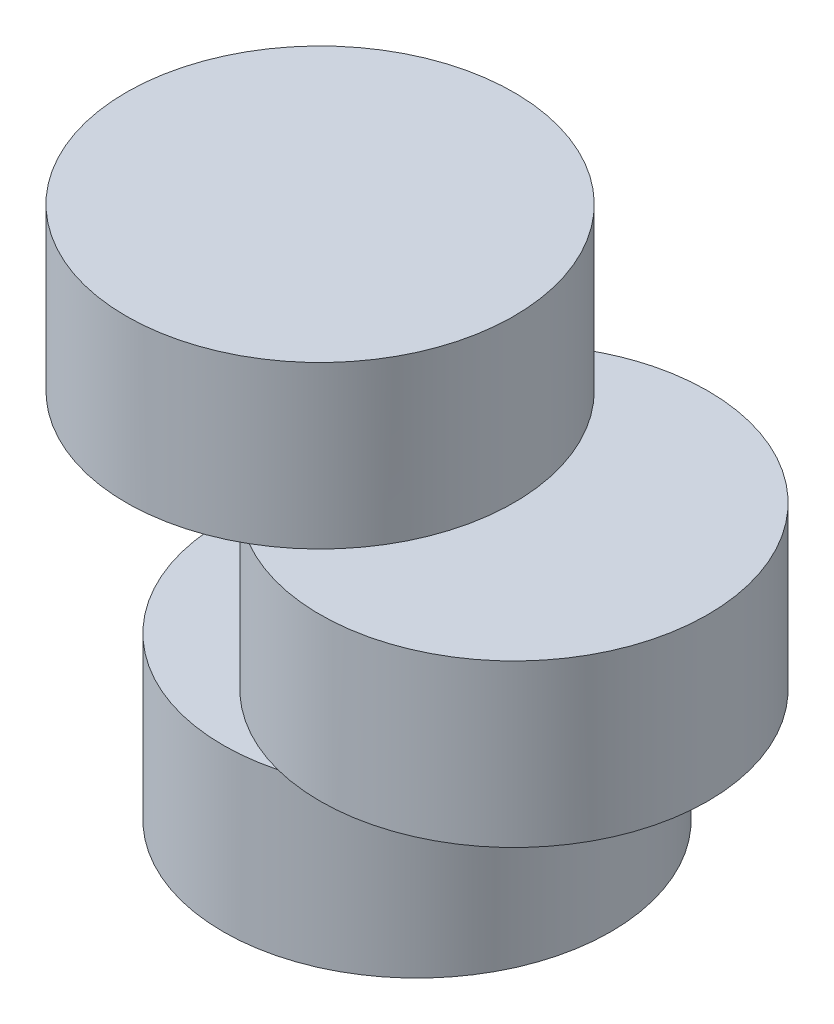
SolidWorks part; units mm, degrees
ref_plane "Front Plane" through (0, 0, 0) normal (0, 0, 1) x (1, 0, 0)
ref_plane "Top Plane" through (0, 0, 0) normal (0, 1, 0) x (1, 0, 0)
ref_plane "Right Plane" through (0, 0, 0) normal (1, 0, 0) x (0, 0, -1)
sketch "Sketch1" plane through (0, 0, 0) normal (0, 1, 0) x (1, 0, 0)
  circle A0 centre (0, 0) radius 12
  dimension "D1" = 24
extrude "Boss-Extrude1" add sketch "Sketch1" along normal blind 10
sketch "Sketch2" plane through (0, 10, 0) normal (0, 1, 0) x (1, 0, 0)
  line L0 (0, 0) -> (6, 0) construction
  circle A0 centre (6, 0) radius 12
  dimension "D2" = 24
  dimension "D1" = 6
extrude "Boss-Extrude2" add sketch "Sketch2" along normal blind 10
sketch "Sketch3" plane through (0, 20, 0) normal (0, 1, 0) x (1, 0, 0)
  line L0 (0, 0) -> (-6, 0) construction
  circle A3 centre (-6, 0) radius 12
  dimension "D2" = 24
  dimension "D1" = 6
extrude "Boss-Extrude3" add sketch "Sketch3" along normal blind 10
sketch "Sketch4" plane through (0, 0, 0) normal (0, -1, 0) x (1, 0, 0)
  line L1 (-2.1801, -2.0608) -> (-2.1801, 2.0608)
  arc A0 (-2.1801, -2.0608) -> (-2.1801, 2.0608) centre (0, 0) ccw
  dimension "D1" = 6
extrude "Cut-Extrude1" cut sketch "Sketch4" against normal blind 6
